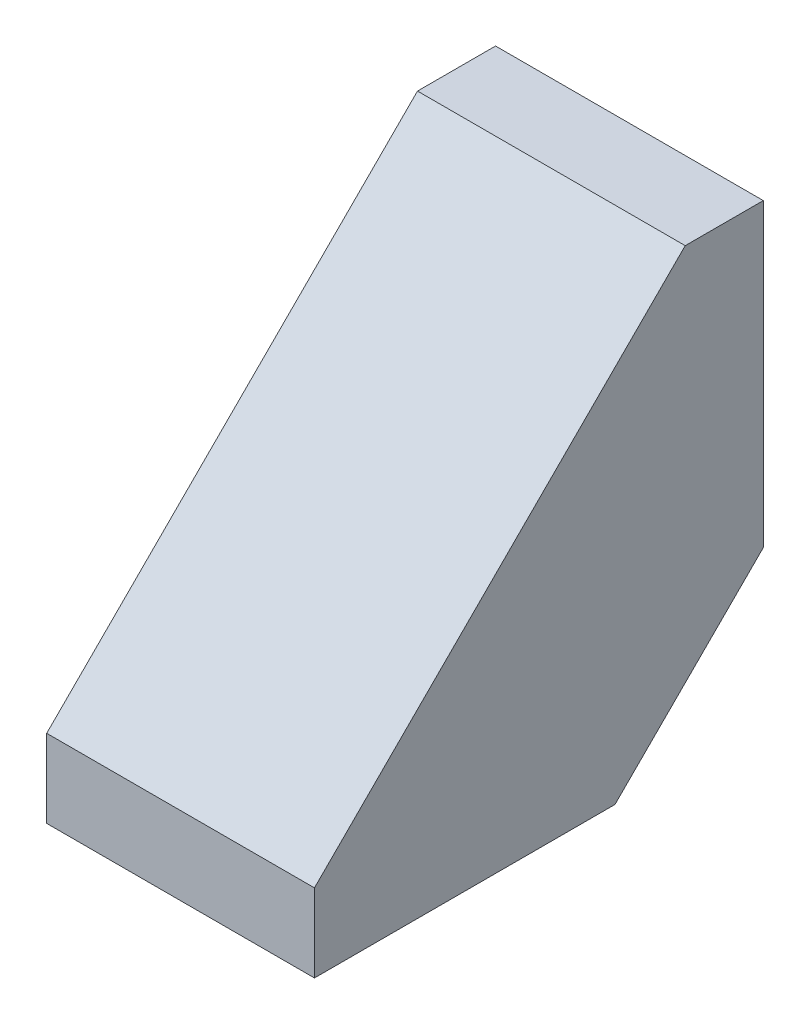
SolidWorks part; units mm, degrees
ref_plane "Front Plane" through (0, 0, 0) normal (0, 0, 1) x (1, 0, 0)
ref_plane "Top Plane" through (0, 0, 0) normal (0, 1, 0) x (1, 0, 0)
ref_plane "Right Plane" through (0, 0, 0) normal (1, 0, 0) x (0, 0, -1)
sketch "Sketch1" plane through (0, 0, 0) normal (1, 0, 0) x (0, 0, -1)
  line L0 (0, 0) -> (38.5, 0)
  line L1 (38.5, 0) -> (57.5, 19)
  line L2 (57.5, 19) -> (57.5, 57.5)
  line L3 (57.5, 57.5) -> (47.5, 57.5)
  line L4 (47.5, 57.5) -> (0, 10)
  line L5 (0, 10) -> (0, 0)
  dimension "D1" = 38.5
  dimension "D2" = 57.5
  dimension "D3" = 135
  dimension "D4" = 10
extrude "Boss-Extrude1" add sketch "Sketch1" along normal blind 34.3
